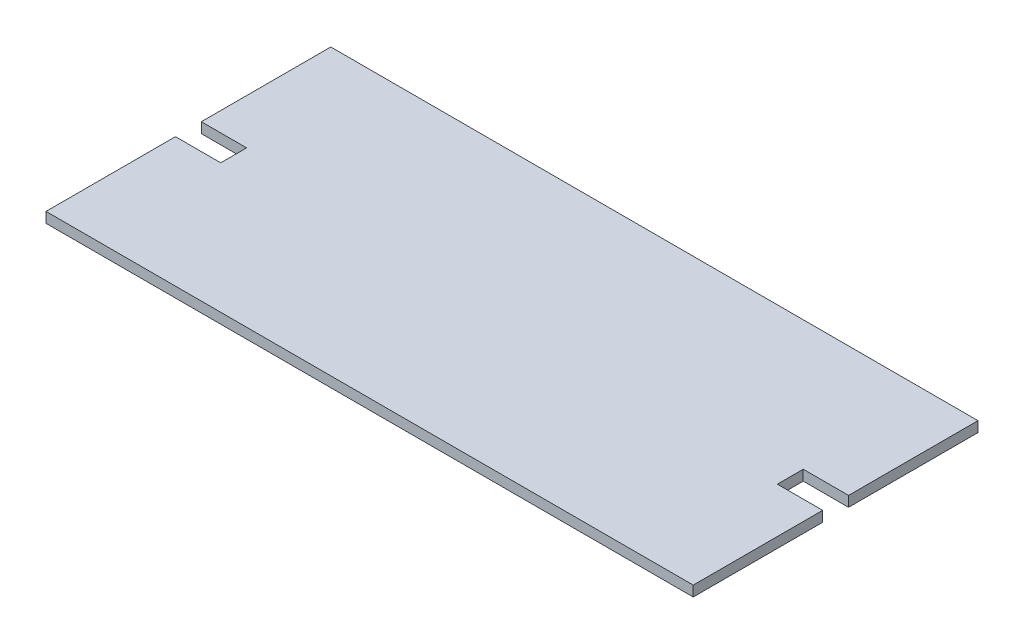
SolidWorks part; units mm, degrees
ref_plane "Front Plane" through (0, 0, 0) normal (0, 0, 1) x (1, 0, 0)
ref_plane "Top Plane" through (0, 0, 0) normal (0, 1, 0) x (1, 0, 0)
ref_plane "Right Plane" through (0, 0, 0) normal (1, 0, 0) x (0, 0, -1)
sketch "Sketch2" plane through (0, 0, 0) normal (0, 1, 0) x (1, 0, 0)
  line L1 (-50, 22) -> (50, 22)
  line L2 (-50, 22) -> (-50, -22)
  line L3 (-50, -22) -> (50, -22)
  line L4 (50, 22) -> (50, -22)
  line L5 (-50, 22) -> (50, -22) construction
  line L6 (-50, -22) -> (50, 22) construction
  line L7 (-50, 2) -> (-43, 2)
  line L8 (-50, 2) -> (-50, -2)
  line L9 (-50, -2) -> (-43, -2)
  line L10 (-43, 2) -> (-43, -2)
  line L11 (50, 2) -> (43, 2)
  line L12 (50, 2) -> (50, -2)
  line L13 (50, -2) -> (43, -2)
  line L14 (43, 2) -> (43, -2)
  point P0 (0, 0)
  point P14 (-43, 0)
  point P15 (43, 0)
  dimension "D1" = 100
  dimension "D2" = 44
  dimension "D3" = 7
  dimension "D4" = 7
  dimension "D5" = 4
  dimension "D6" = 4
extrude "Boss-Extrude1" add sketch "Sketch2" along normal blind 1.6 contours L14 L11 L4 L1 L2 L7 L10 L9 L3 L13
equation "\"D4@Sketch2\"=\"D3@Sketch2\""
equation "\"D6@Sketch2\"=\"D5@Sketch2\""
